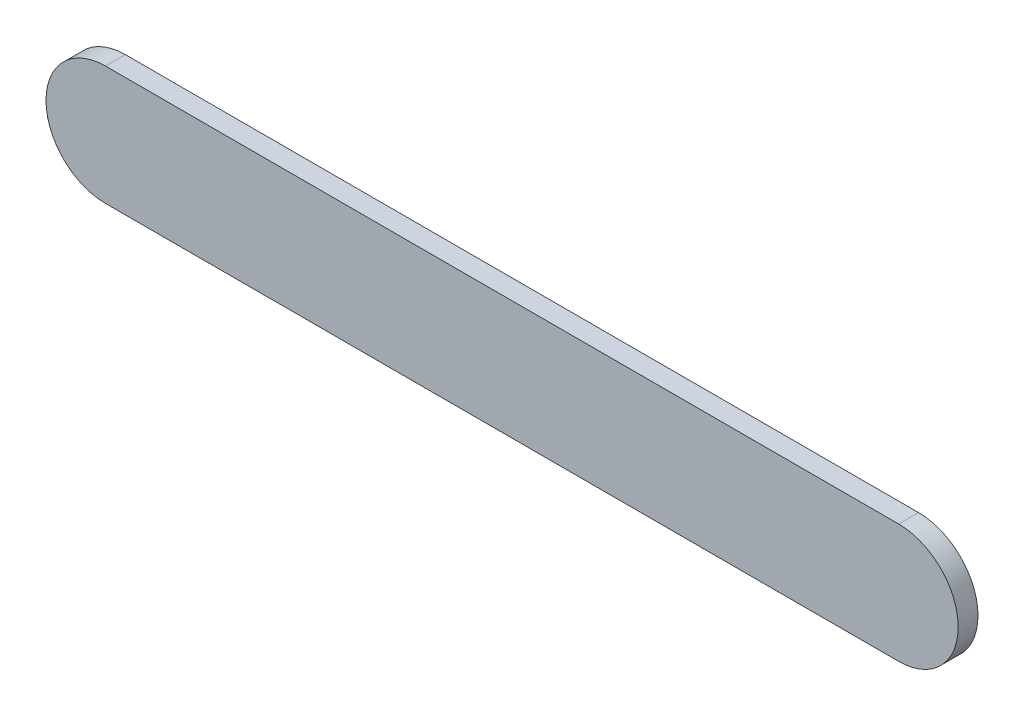
SolidWorks part; units mm, degrees
material "leg"
ref_plane "前视基准面" through (0, 0, 0) normal (0, 0, 1) x (1, 0, 0)
ref_plane "上视基准面" through (0, 0, 0) normal (0, 1, 0) x (1, 0, 0)
ref_plane "右视基准面" through (0, 0, 0) normal (1, 0, 0) x (0, 0, -1)
other "质心 (COM)"
other "Configuration Table"
sketch "草图1" plane through (0, 0, 0) normal (0, 0, 1) x (1, 0, 0)
  line L0 (0, 0) -> (400, 0)
  line L1 (0, 30) -> (400, 30)
  line L2 (400, -30) -> (0, -30)
  circle A0 centre (0, 0) radius 30
  circle A1 centre (400, 0) radius 30
  dimension "D1" = 60
  dimension "D3" = 60
  dimension "D2" = 400
extrude "凸台-拉伸1" add sketch "草图1" along normal blind 10
